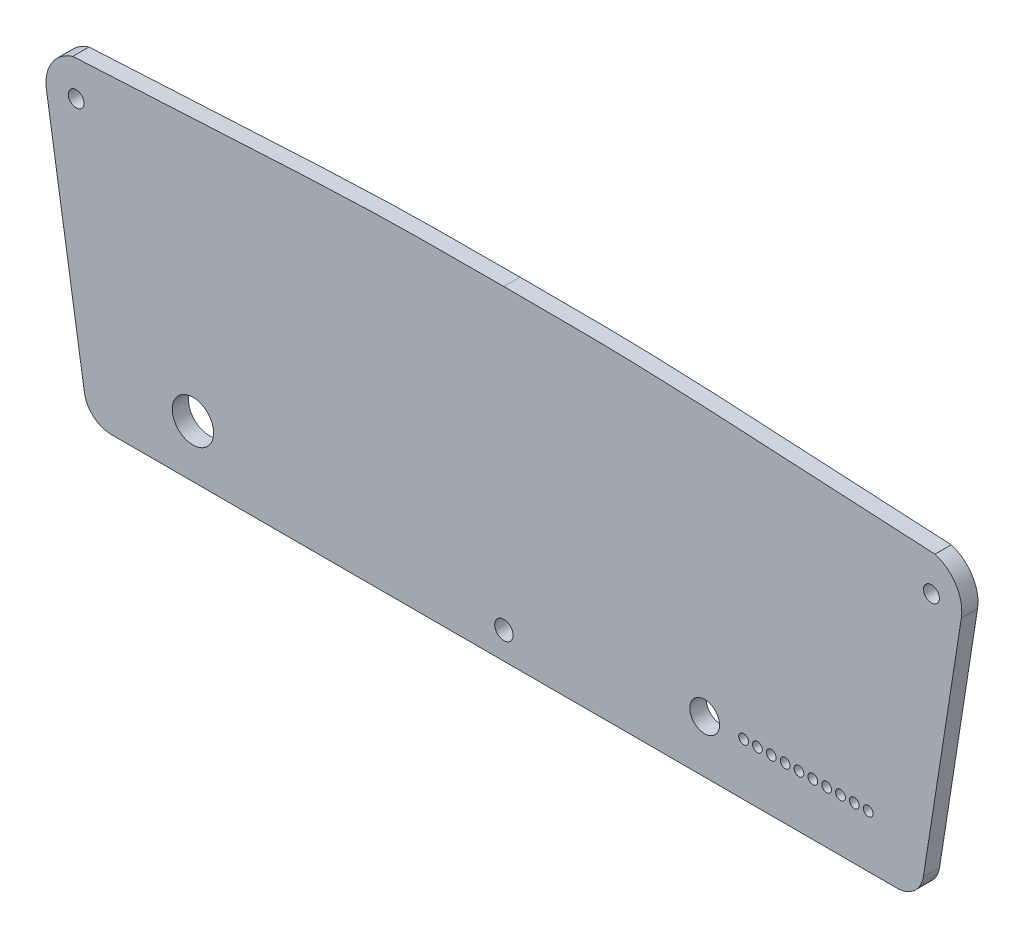
SolidWorks part; units mm, degrees
ref_plane "Alzado" through (0, 0, 0) normal (0, 0, 1) x (1, 0, 0)
ref_plane "Planta" through (0, 0, 0) normal (0, 1, 0) x (1, 0, 0)
ref_plane "Vista lateral" through (0, 0, 0) normal (1, 0, 0) x (0, 0, -1)
sketch "Croquis1" plane through (0, 0, 0) normal (0, 0, 1) x (1, 0, 0)
  line L0 (72.621, -42.7139) -> (-72.621, -42.7139)
  line L1 (79.7182, 14.2861) -> (-79.7182, 14.2861) construction
  line L2 (0, 14.2861) -> (0, 17.2861) construction
  line L3 (-77.7935, 17.2861) -> (77.7935, 17.2861) construction
  line L4 (0, -40.4126) -> (0, 34.1548) construction
  line L5 (-25, 41.2162) -> (-25, -46.3712) construction
  line L6 (-77.5611, -38.4855) -> (-84.5891, 6.5113)
  line L11 (25, 41.2162) -> (25, -46.3712) construction
  line L14 (77.5611, -38.4855) -> (84.5891, 6.5113)
  arc A0 (84.5891, 6.5113) -> (79.7182, 14.2861) centre (77.6729, 7.5915) ccw
  arc A1 (77.5611, -38.4855) -> (72.621, -42.7139) centre (72.621, -37.7139) cw
  arc A2 (-77.5611, -38.4855) -> (-72.621, -42.7139) centre (-72.621, -37.7139) ccw
  arc A3 (-84.5891, 6.5113) -> (-79.7182, 14.2861) centre (-77.6729, 7.5915) cw
  conic Q0 (79.7182, 14.2861) -> (0, 17.2861) control (25, 17.2861) rho 0.75
  conic Q1 (-79.7182, 14.2861) -> (0, 17.2861) control (-25, 17.2861) rho 0.75
  point P15 (-84.627, 12.5288)
  point P27 (0, -42.7139)
  point P28 (0, -42.7139)
  point P40 (0, 9.5288)
  point P61 (0, -42.7139)
  point P62 (84.627, 12.5288)
  dimension "D1" = 5
  dimension "D2" = 7
  dimension "D4" = 60
  dimension "D3" = 3
extrude "Saliente-Extruir3" add sketch "Croquis1" along normal blind 3 contours Q0 Q1 A3 L6 A2 L0 A1 L14 A0
sketch "Croquis10" plane through (0, 0, 0) normal (0, 0, -1) x (-1, 0, 0)
  line L0 (-79.055, -3) -> (-70, 10.8116)
  line L1 (79.055, -3) -> (70, 10.8116)
  line L2 (74.588, 4.2933) -> (83.6049, 11.3079) construction
  line L3 (0, -3) -> (92.9677, -3) construction
  line L4 (-70, 32.4884) -> (-70, -57.6963) construction
  line L5 (70, -55.635) -> (70, -62.635) construction
  line L6 (-80.637, 7.1286) -> (-73.609, -37.8682)
  line L7 (-72.621, -38.7139) -> (72.621, -38.7139)
  line L8 (73.609, -37.8682) -> (80.637, 7.1286)
  line L9 (-79.055, -3) -> (-73.609, -37.8682)
  line L10 (-72.621, -38.7139) -> (72.621, -38.7139)
  line L11 (73.609, -37.8682) -> (79.055, -3)
  line L12 (0, -66.0706) -> (0, 45.5866) construction
  line L13 (-74.5275, 3.9058) -> (-83.6049, 11.3079)
  line L14 (0, -37.7139) -> (-24.3325, -37.7139) construction
  line L15 (-72.621, -42.7139) -> (72.621, -42.7139) construction
  line L16 (-24.3325, -26.0292) -> (-24.3325, -3) construction
  line L17 (-24.3325, -3) -> (-68.8422, -3) construction
  line L18 (-24.3325, -63.0295) -> (-68.8422, -63.0295) construction
  line L19 (-68.8422, -26.4303) -> (-68.8422, -3) construction
  line L20 (-42.8422, -63.0295) -> (-42.8422, -3) construction
  line L21 (-42.8422, -33.0147) -> (-68.8422, -33.0147) construction
  line L22 (-46.8822, -33.0147) -> (-27.3692, -33.0147) construction
  arc A0 (-79.7182, 14.2861) -> (-84.5891, 6.5113) centre (-77.6729, 7.5915) ccw construction
  arc A1 (84.5891, 6.5113) -> (79.7182, 14.2861) centre (77.6729, 7.5915) ccw construction
  arc A8 (-78.9106, 10.3243) -> (-80.637, 7.1286) centre (-77.6729, 7.5915) ccw
  arc A9 (-73.609, -37.8682) -> (-72.621, -38.7139) centre (-72.621, -37.7139) ccw
  arc A10 (72.621, -38.7139) -> (73.609, -37.8682) centre (72.621, -37.7139) ccw
  arc A11 (80.637, 7.1286) -> (78.9106, 10.3243) centre (77.6729, 7.5915) ccw
  arc A13 (-73.609, -37.8682) -> (-72.621, -38.7139) centre (-72.621, -37.7139) ccw
  arc A14 (72.621, -38.7139) -> (73.609, -37.8682) centre (72.621, -37.7139) ccw
  spline S4 degree 3 poles (2127.4277, 3107.9879) (1321.8072, -103.3293) (691.7435, -22.6635) (52.6222, 11.7513) (46.0499, 12.1034) (36.1891, 12.5892) (32.9019, 12.7438) (26.3256, 13.0031) (23.0364, 13.1028) (16.455, 13.2247) (13.1641, 13.2517) (-251.0773, 14.4861) (-512.4874, -58.3996) (-748.9997, 3882.2691) knots -23.81136 -23.81136 -23.81136 -23.81136 0.25 0.25 0.5 0.5 0.625 0.625 0.75 0.75 0.875 0.875 10.786587 10.786587 10.786587 10.786587 only from (78.9106, 10.3243) to (0, 13.2861)
  spline S5 degree 3 poles (468.6965, 896.6433) (312.9806, -13.5531) (151.4662, 14.0208) (-13.1641, 13.2517) (-16.455, 13.2247) (-23.0364, 13.1028) (-26.3256, 13.0031) (-32.9019, 12.7438) (-36.1891, 12.5892) (-46.0499, 12.1034) (-52.6222, 11.7513) (-374.041, -5.5562) (-688.2719, -34.056) (-1023.8404, 337.5944) knots -6.00309 -6.00309 -6.00309 -6.00309 0.125 0.125 0.25 0.25 0.375 0.375 0.5 0.5 0.75 0.75 12.726363 12.726363 12.726363 12.726363 only from (0, 13.2861) to (-78.9106, 10.3243)
  spline S6 degree 3 poles (70, 10.8116) (66.3982, 11.008) (62.7964, 11.2034) (52.6222, 11.7513) (46.0499, 12.1034) (36.1891, 12.5892) (32.9019, 12.7438) (26.3256, 13.0031) (23.0364, 13.1028) (16.455, 13.2247) (13.1641, 13.2517) (6.5821, 13.2825) (3.2911, 13.2861) (0, 13.2861) knots 0.112988 0.112988 0.112988 0.112988 0.25 0.25 0.5 0.5 0.625 0.625 0.75 0.75 0.875 0.875 1 1 1 1
  point P8 (-79.055, -3)
  point P9 (-70, 10.8116)
  point P35 (-79.0662, 7.6069)
  point P37 (74.588, 4.2933)
  point P40 (79.0965, 7.8006)
  point P55 (-55.8422, -33.0147)
  point P61 (-46.8822, -33.0147)
  point P62 (-49.4422, -33.0147)
  point P63 (-52.0022, -33.0147)
  point P64 (-54.5622, -33.0147)
  point P65 (-54.5622, -33.0147)
  point P66 (-55.8422, -33.0147)
  point P67 (-59.6822, -33.0147)
  point P68 (-62.2422, -33.0147)
  point P69 (-64.8022, -33.0147)
  point P72 (-37.1257, -33.0147)
  point P73 (-44.3222, -33.0147)
  point P75 (-67.3622, -33.0147)
  dimension "D2" = 70
  dimension "D3" = 70
  dimension "D4" = 3
  dimension "D5" = 5
  dimension "D1" = 4
hole_wizard "Taladro de margen para #31" positions "Croquis3D1" profile "Croquis13" hole size "#3" standard "Ansi Inch" end condition through all
sketch3d "Croquis3D1"
  point P0 (-79.0965, 7.8006, 0)
  point P3 (79.0662, 7.6069, 0)
sketch "Croquis13" plane through (-79.0965, 7.8006, 0) normal (1, 0, 0) x (0, 1, 0)
  line L0 (0, 0) -> (0, 3)
  line L1 (0, 3) -> (1.4605, 3)
  line L2 (1.4605, 3) -> (1.4605, 0)
  line L5 (1.4605, 0) -> (0, 0)
  line L11 (0, -6.35) -> (0, 107.95) construction
  dimension "Diámetro de taladro hasta el siguiente" = 2.921
  dimension "Profundidad de taladro hasta el siguiente" = 3
hole_wizard "Taladro de margen para M31" positions "Croquis3D3" profile "Croquis15" hole size "M3" standard "Ansi Metric" end condition through all
sketch3d "Croquis3D3"
  point P0 (0, -37.7139, 0)
sketch "Croquis15" plane through (0, -37.7139, 0) normal (1, 0, 0) x (0, 1, 0)
  line L0 (0, 0) -> (0, 3)
  line L1 (0, 3) -> (1.7, 3)
  line L2 (1.7, 3) -> (1.7, 0)
  line L5 (1.7, 0) -> (0, 0)
  line L11 (0, -6.35) -> (0, 107.95) construction
  dimension "Diámetro de taladro hasta el siguiente" = 3.4
  dimension "Profundidad de taladro hasta el siguiente" = 3
hole_wizard "Taladro de margen para M51" positions "Croquis3D6" profile "Croquis18" hole size "M5" standard "Ansi Metric" end condition through all
sketch3d "Croquis3D6"
  point P0 (37.1257, -33.0147, 0)
sketch "Croquis18" plane through (37.1257, -33.0147, 0) normal (1, 0, 0) x (0, 1, 0)
  line L0 (0, 0) -> (0, 3)
  line L1 (0, 3) -> (2.75, 3)
  line L2 (2.75, 3) -> (2.75, 0)
  line L5 (2.75, 0) -> (0, 0)
  line L11 (0, -6.35) -> (0, 107.95) construction
  dimension "Diámetro de taladro hasta el siguiente" = 5.5
  dimension "Profundidad de taladro hasta el siguiente" = 3
hole_wizard "Taladro de margen para M1.61" positions "Croquis3D7" profile "Croquis19" hole size "M1.6" standard "Ansi Metric" end condition through all
sketch3d "Croquis3D7"
  line L0 (42.8422, -33.0147, 0) -> (68.8422, -33.0147, 0) construction
  circle A0 centre (55.8422, -33.0147, 0) radius 1.28 construction
  point P0 (44.3222, -33.0147, 0)
  point P3 (46.8822, -33.0147, 0)
  point P6 (49.4422, -33.0147, 0)
  point P9 (52.0022, -33.0147, 0)
  point P12 (54.5622, -33.0147, 0)
  point P15 (57.1222, -33.0147, 0)
  point P19 (55.8422, -33.0147, -1.28)
  point P22 (59.6822, -33.0147, 0)
  point P25 (62.2422, -33.0147, 0)
  point P28 (64.8022, -33.0147, 0)
  point P31 (67.3622, -33.0147, 0)
  point P34 (57.1222, -33.0147, 0)
sketch "Croquis19" plane through (44.3222, -33.0147, 0) normal (1, 0, 0) x (0, 1, 0)
  line L0 (0, 0) -> (0, 3)
  line L1 (0, 3) -> (0.9, 3)
  line L2 (0.9, 3) -> (0.9, 0)
  line L5 (0.9, 0) -> (0, 0)
  line L11 (0, -6.35) -> (0, 107.95) construction
  dimension "Diámetro de taladro hasta el siguiente" = 1.8
  dimension "Profundidad de taladro hasta el siguiente" = 3
sketch "Croquis20" plane through (0, 0, 3) normal (0, 0, 1) x (1, 0, 0)
  line L0 (27.3692, -33.0147) -> (-89.5623, -33.0147) construction
  circle A0 centre (-57.4968, -33.0147) radius 3.825
  point P3 (-57.4968, -33.0147)
  dimension "D1" = 7.65
extrude "Cortar-Extruir1" cut sketch "Croquis20" against normal blind 10
sketch "Croquis21" plane through (0, 0, 3) normal (0, 0, 1) x (1, 0, 0)
  line L0 (-20, -25.1874) -> (20, -25.1874) construction
  line L1 (0, 0) -> (0, -54.4601) construction
  text T0 "Pablo Martínez García\r\n2015-2016" font "Vladimir Script" height 3.5
